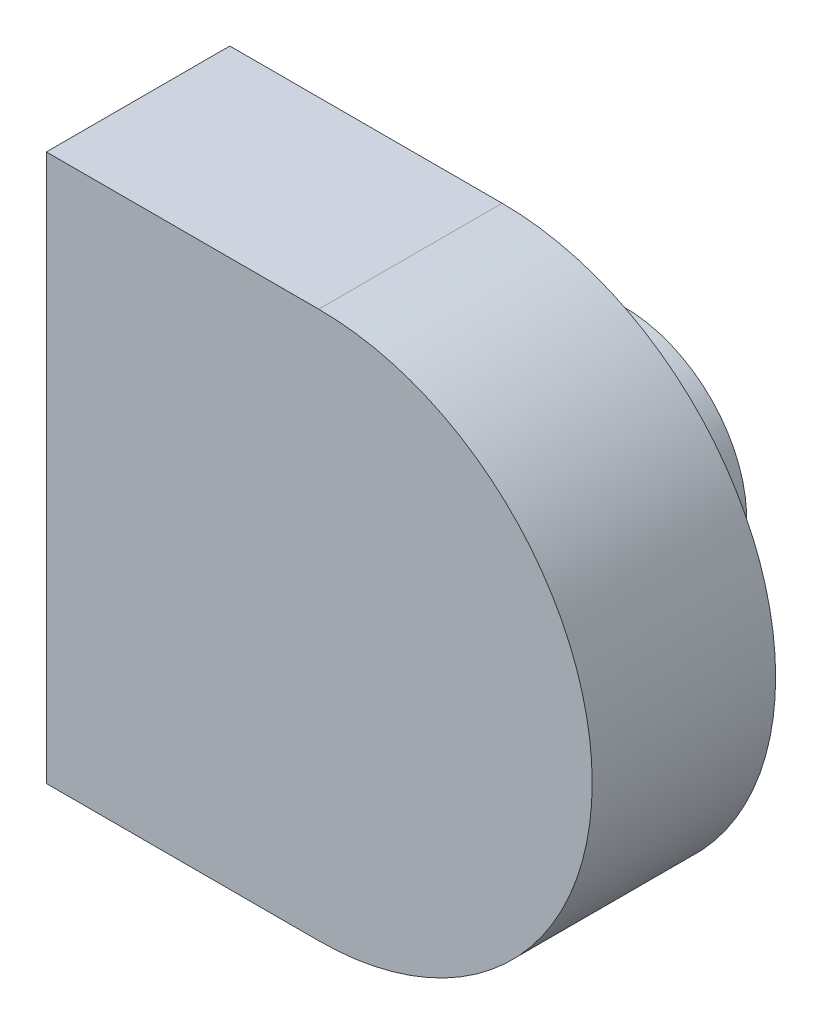
SolidWorks part; units mm, degrees
ref_plane "前视基准面" through (0, 0, 0) normal (0, 0, 1) x (1, 0, 0)
ref_plane "上视基准面" through (0, 0, 0) normal (0, 1, 0) x (1, 0, 0)
ref_plane "右视基准面" through (0, 0, 0) normal (1, 0, 0) x (0, 0, -1)
other "Configuration Table"
sketch "草图1" plane through (0, 0, 0) normal (0, 0, 1) x (1, 0, 0)
  line L1 (0, 0) -> (189.06, 0)
  line L2 (0, 0) -> (0, 44.73)
  line L3 (0, 44.73) -> (189.06, 44.73)
  line L4 (189.06, 0) -> (189.06, 44.73)
  dimension "D1" = 189.06
  dimension "D2" = 44.73
extrude "凸台-拉伸1" add sketch "草图1" along normal blind 15
sketch "草图2" plane through (0, 0, 0) normal (0, 0, 1) x (1, 0, 0)
  line L0 (0, 22.365) -> (6, 22.365) construction
  line L1 (0, 44.73) -> (0, 0) construction
  line L2 (49.87, 22.365) -> (49.87, 38.3624) construction
  line L3 (49.87, 22.365) -> (49.87, -29.0061) construction
  line L4 (6, 22.365) -> (91.74, 22.365) construction
  line L5 (91.74, 22.365) -> (93.74, 22.365) construction
  line L6 (189.06, 44.73) -> (0, 44.73) construction
  arc A2 (0.0194, 23.7552) -> (2.9047, 39.1362) centre (49.87, 22.365) cw
  arc A12 (92.412, 17.0724) -> (89.7396, 6.609) centre (49.87, 22.365) cw
  arc A13 (92.0308, 30.1305) -> (92.6094, 19.0214) centre (49.87, 22.365) cw
  arc A14 (7.0167, 23.56) -> (9.4969, 36.7821) centre (49.87, 22.365) cw
  arc A15 (11.5101, 3.2246) -> (7.5633, 15.4382) centre (49.87, 22.365) cw
  circle A16 centre (9.0186, 9.365) radius 1
  circle A17 centre (7, 22.365) radius 1
  circle A18 centre (9.0186, 35.365) radius 1
  circle A19 centre (90.7214, 9.365) radius 1
  circle A20 centre (90.7214, 35.365) radius 1
  circle A21 centre (92.74, 22.365) radius 1
  point P52 (39.3691, 16.6488)
  dimension "D1" = 42.87
  dimension "D2" = 42.87
  dimension "D4" = 2
  dimension "D5" = 2
  dimension "D6" = 2
  dimension "D7" = 2
  dimension "D8" = 2
  dimension "D9" = 13
  dimension "D10" = 13
  dimension "D11" = 13
  dimension "D3" = 2
  dimension "D14" = 42.87
  dimension "D15" = 42.87
  dimension "D12" = 13
  dimension "D13" = 7
  dimension "D16" = 32.87
  dimension "D17" = 22.365
sketch "草图3" plane through (0, 0, 0) normal (0, 0, -1) x (-1, 0, 0)
  line L0 (0, 22.365) -> (-6, 22.365) construction
  line L1 (0, 22.365) -> (-224.1604, 22.365) construction
  line L2 (-189.06, 44.73) -> (0, 44.73) construction
  line L3 (-22.27, 32.365) -> (-30.9303, 27.365)
  line L4 (-30.9303, 27.365) -> (-30.9303, 17.365)
  line L5 (-30.9303, 17.365) -> (-22.27, 12.365)
  line L6 (-22.27, 12.365) -> (-13.6097, 17.365)
  line L7 (-13.6097, 17.365) -> (-13.6097, 27.365)
  line L8 (-13.6097, 27.365) -> (-22.27, 32.365)
  line L9 (0, 44.73) -> (0, 0) construction
  circle A0 centre (-22.27, 22.365) radius 10
  circle A1 centre (-22.27, 22.365) radius 8.6603 construction
  circle A3 centre (-22.27, 22.365) radius 18
  point P2 (-22.27, 22.365)
  dimension "D2" = 20
  dimension "D3" = 22.27
  dimension "D1" = 22.365
sketch "草图4" plane through (0, 0, 15) normal (0, 0, 1) x (1, 0, 0)
  line L0 (22.27, 44.73) -> (189.06, 44.73)
  line L1 (189.06, 44.73) -> (189.06, 0)
  line L2 (189.06, 0) -> (189.06, 44.73) construction
  line L3 (189.06, 0) -> (22.27, 0)
  arc A3 (22.27, 0) -> (22.27, 44.73) centre (22.27, 22.365) ccw
extrude "切除-拉伸4" cut sketch "草图4" against normal up to next
sketch "草图6" plane through (0, 0, 0) normal (0, 0, -1) x (-1, 0, 0)
  line L3 (0, 44.73) -> (-22.27, 44.73)
  line L4 (-22.27, 0) -> (0, 0)
  line L5 (0, 0) -> (0, 44.73)
  line L8 (0, 0) -> (0, 44.73)
  circle A0 centre (-22.27, 22.365) radius 10 construction
  circle A3 centre (-22.27, 22.365) radius 10
  arc A5 (-22.27, 44.73) -> (-22.27, 0) centre (-22.27, 22.365) ccw
  arc A6 (-22.27, 44.73) -> (-22.27, 0) centre (-22.27, 22.365) ccw
  dimension "D2" = 20
  dimension "D1" = 0
extrude "凸台-拉伸2" add sketch "草图6" along normal blind 10 contours A3
sketch "草图7" plane through (0, 0, -10) normal (0, 0, -1) x (-1, 0, 0)
  circle A0 centre (-22.27, 22.365) radius 10 construction
  circle A1 centre (-22.27, 22.365) radius 10 construction
  circle A2 centre (-22.27, 22.365) radius 7 construction
  circle A3 centre (-22.27, 29.365) radius 1
  circle A4 centre (-15.27, -108.5766) radius 1
  circle A5 centre (-153.2116, -115.5766) radius 1
  circle A6 centre (-160.2116, 22.365) radius 1
  point P15 (-87.7408, -43.1058)
  dimension "D1" = 14
  dimension "D2" = 2
  dimension "D3" = 4
extrude "切除-拉伸6" cut sketch "草图7" against normal blind 5
sketch "草图8" plane through (0, 0, 0) normal (0, 0, -1) x (-1, 0, 0)
  circle A0 centre (-22.27, 22.365) radius 10 construction
  circle A1 centre (-22.27, 22.365) radius 10
  circle A2 centre (-22.27, 22.365) radius 12
  dimension "D1" = 24
extrude "凸台-拉伸3" add sketch "草图8" along normal blind 2.5
